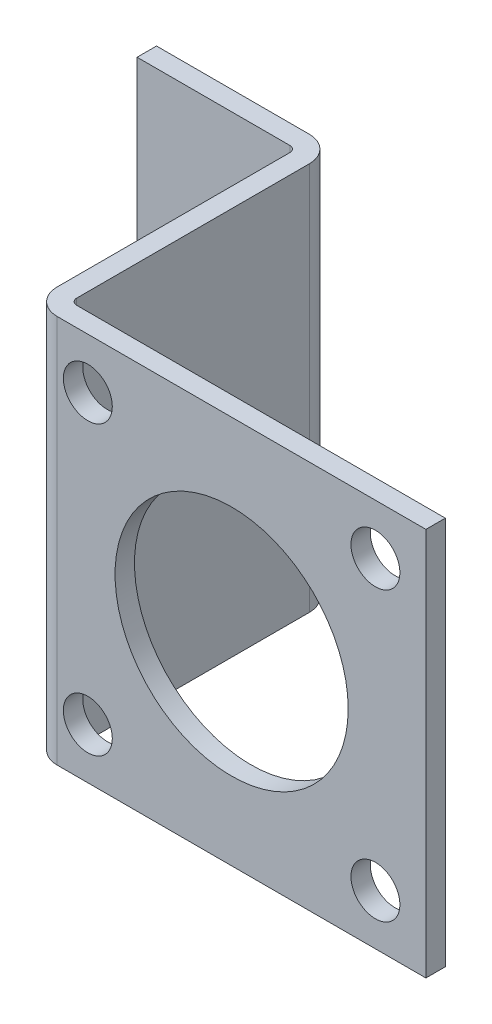
SolidWorks part; units mm, degrees
ref_plane "Front Plane" through (0, 0, 0) normal (0, 0, 1) x (1, 0, 0)
ref_plane "Top Plane" through (0, 0, 0) normal (0, 1, 0) x (1, 0, 0)
ref_plane "Right Plane" through (0, 0, 0) normal (1, 0, 0) x (0, 0, -1)
sketch "Sketch1" plane through (0, 0, 0) normal (0, 0, 1) x (1, 0, 0)
  line L1 (-28.4999, -28.4999) -> (28.4999, -28.4999) construction
  line L2 (-28.4999, -28.4999) -> (-28.4999, 28.4999) construction
  line L3 (-28.4999, 28.4999) -> (28.4999, 28.4999) construction
  line L4 (28.4999, -28.4999) -> (28.4999, 28.4999) construction
  line L5 (-28.4999, -28.4999) -> (28.4999, 28.4999) construction
  line L6 (-28.4999, 28.4999) -> (28.4999, -28.4999) construction
  line L7 (-23.5, -23.5) -> (23.5, -23.5) construction
  line L8 (-23.5, -23.5) -> (-23.5, 23.5) construction
  line L9 (-23.5, 23.5) -> (23.5, 23.5) construction
  line L10 (23.5, -23.5) -> (23.5, 23.5) construction
  line L11 (-23.5, -23.5) -> (23.5, 23.5) construction
  line L12 (-23.5, 23.5) -> (23.5, -23.5) construction
  circle A0 centre (0, 0) radius 19.05
  circle A1 centre (23.5, 23.5) radius 4
  circle A2 centre (23.5, -23.5) radius 4
  circle A3 centre (-23.5, -23.5) radius 4
  circle A4 centre (-23.5, 23.5) radius 4
  dimension "D1" = 38.1
  dimension "D7" = 8
  dimension "D2" = 56.9999
  dimension "D6" = 47
sketch "Sketch2" plane through (0, 0, 0) normal (0, 1, 0) x (1, 0, 0)
  line L0 (31.75, 0) -> (-28.4999, 0)
  line L1 (-32.6909, 4.191) -> (-32.6909, 42.209)
  line L2 (-33.7069, 43.225) -> (-58.6739, 43.225)
  line L3 (31.75, 3.175) -> (-28.4999, 3.175)
  line L4 (-29.5159, 4.191) -> (-29.5159, 42.209)
  line L5 (-33.7069, 46.4) -> (-58.6739, 46.4)
  line L6 (-58.6739, 43.225) -> (-58.6739, 46.4)
  line L7 (31.75, 0) -> (31.75, 3.175)
  line L8 (-28.4999, -10.8428) -> (-28.4999, 10.8428) construction
  arc A0 (-32.6909, 42.209) -> (-33.7069, 43.225) centre (-33.7069, 42.209) ccw
  arc A1 (-28.4999, 0) -> (-32.6909, 4.191) centre (-28.4999, 4.191) cw
  arc A2 (-28.4999, 3.175) -> (-29.5159, 4.191) centre (-28.4999, 4.191) cw
  arc A3 (-29.5159, 42.209) -> (-33.7069, 46.4) centre (-33.7069, 42.209) ccw
  point P19 (-28.4999, 0)
  dimension "D1" = 1.016
  dimension "D2" = 4.191
  dimension "D4" = 46.4
  dimension "D5" = 30.1739
  dimension "D7" = 31.75
  dimension "D3" = 3.175
extrude "Boss-Extrude1" add sketch "Sketch2" along normal mid plane 63.5 contours L5 L6 L2 A0 L1 A1 L0 L7 L3 A2 L4 A3
extrude "Cut-Extrude1" cut sketch "Sketch1" against normal through all both and the other way through all
